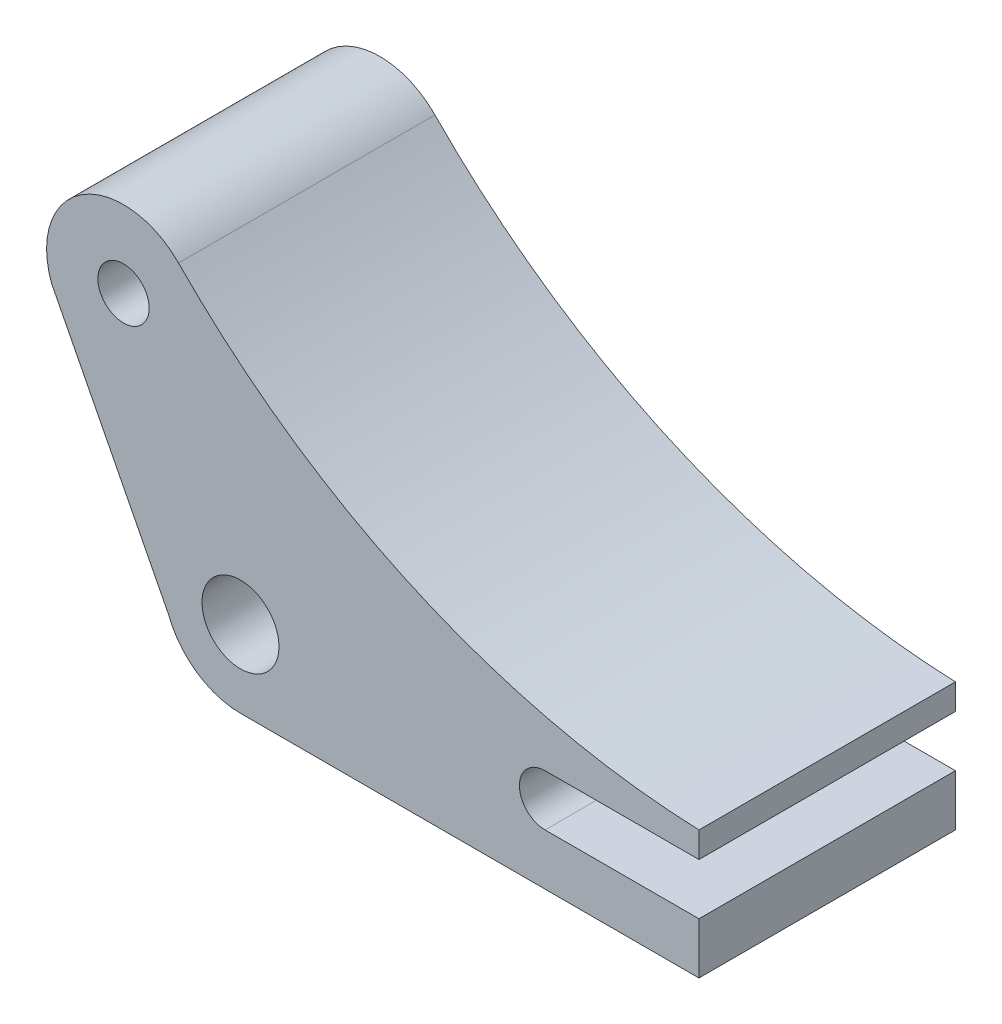
SolidWorks part; units mm, degrees
ref_plane "Front Plane" through (0, 0, 0) normal (0, 0, 1) x (1, 0, 0)
ref_plane "Top Plane" through (0, 0, 0) normal (0, 1, 0) x (1, 0, 0)
ref_plane "Right Plane" through (0, 0, 0) normal (1, 0, 0) x (0, 0, -1)
sketch "Sketch3" plane through (0, 0, 0) normal (0, 0, 1) x (1, 0, 0)
  line L0 (0, -30) -> (178.7618, -30)
  line L1 (0, 0) -> (-45.6137, 88.9909) construction
  line L2 (-28.0166, -10.7271) -> (-73.6303, 78.2638)
  line L3 (178.7618, -30) -> (178.7618, -10)
  line L4 (178.7618, -10) -> (118.7618, -10)
  line L5 (118.7618, -10) -> (118.7618, 10)
  line L6 (118.7618, 10) -> (178.7618, 10)
  line L7 (178.7618, 10) -> (178.7618, 20)
  circle A0 centre (0, 0) radius 15
  arc A1 (0, -30) -> (-28.0166, -10.7271) centre (0, 0) cw
  circle A2 centre (-45.6137, 88.9909) radius 10
  arc A4 (118.7618, -10) -> (118.7618, 10) centre (118.7618, 0) cw
  arc A5 (-24.1706, 109.9717) -> (-70.6807, 72.5092) centre (-45.6137, 88.9909) ccw
  arc A6 (-24.1706, 109.9717) -> (178.7618, 20) centre (190.2604, 319.7796) ccw
  point P19 (-254.8805, 129.8913)
  point P20 (0, 0)
  dimension "D1" = 30
  dimension "D5" = 20
  dimension "D6" = 30
  dimension "D7" = 20
  dimension "D10" = 10
  dimension "D11" = 300
  dimension "D3" = 178.7618
  dimension "D4" = 28.0166
  dimension "D8" = 45.6137
  dimension "D9" = 10
extrude "Boss-Extrude1" add sketch "Sketch3" along normal mid plane 100
